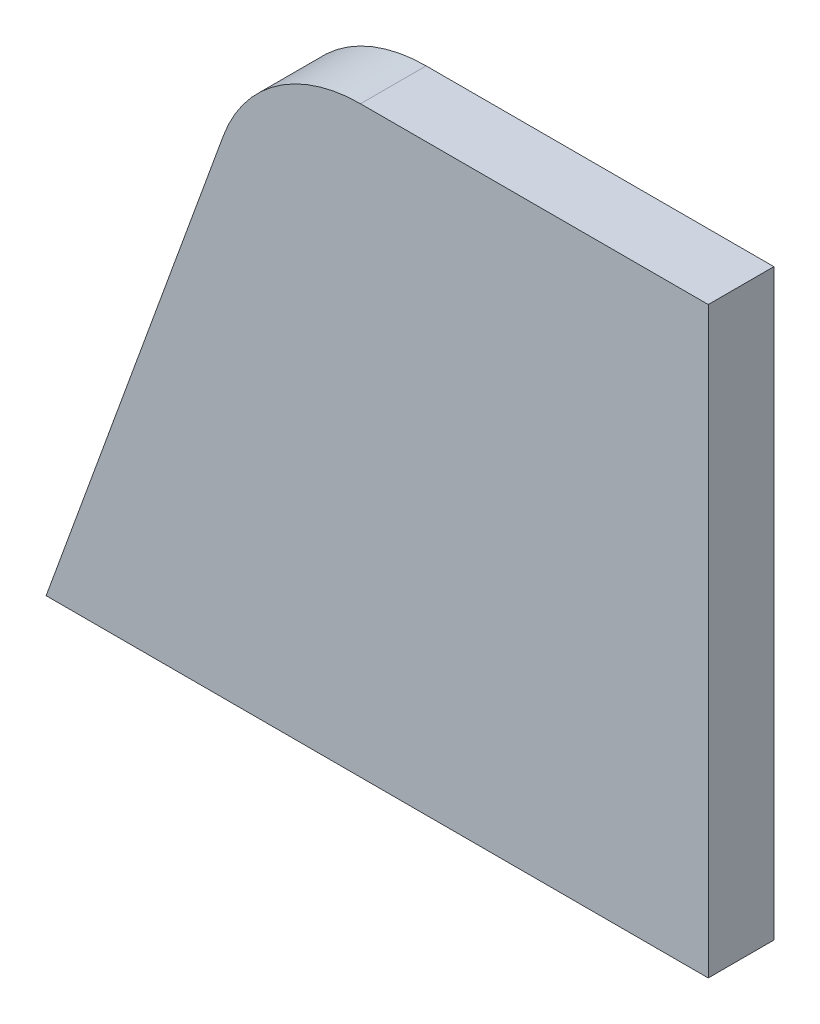
SolidWorks part; units mm, degrees
material "Glass"
ref_plane "Front Plane" through (0, 0, 0) normal (0, 0, 1) x (1, 0, 0)
ref_plane "Top Plane" through (0, 0, 0) normal (0, 1, 0) x (1, 0, 0)
ref_plane "Right Plane" through (0, 0, 0) normal (1, 0, 0) x (0, 0, -1)
sketch "Sketch1" plane through (0, 0, 0) normal (0, 0, 1) x (1, 0, 0)
  line L0 (-304.7973, 1312.6055) -> (-791.3551, -24.2012)
  line L1 (-791.3551, -24.2012) -> (1025.0249, -24.2012)
  line L2 (1025.0249, -24.2012) -> (1025.0249, 1575.7988)
  line L4 (1025.0249, 1575.7988) -> (71.0803, 1575.7988)
  arc A2 (71.0803, 1575.7988) -> (-304.7973, 1312.6055) centre (71.0803, 1175.7988) ccw
  dimension "D4" = 800
  dimension "D1" = 1422.6
  dimension "D2" = 1816.38
  dimension "D3" = 1600
  dimension "D5" = 70
extrude "Boss-Extrude1" add sketch "Sketch1" along normal blind 180 contours L0 L1 L2 L4 A2
